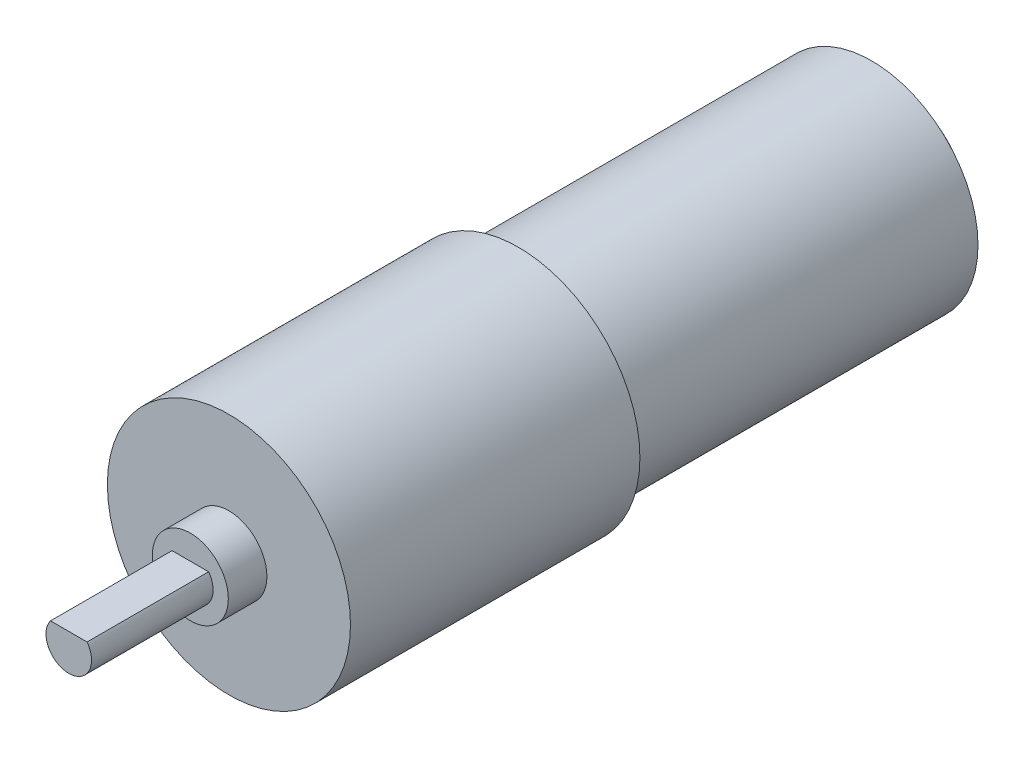
SolidWorks part; units mm, degrees
ref_plane "Front" through (0, 0, 0) normal (0, 0, 1) x (1, 0, 0)
ref_plane "Top" through (0, 0, 0) normal (0, 1, 0) x (1, 0, 0)
ref_plane "Right" through (0, 0, 0) normal (1, 0, 0) x (0, 0, -1)
sketch "Sketch2" plane through (0, 0, 0) normal (0, 0, 1) x (1, 0, 0)
  circle A0 centre (0, 0) radius 8
  dimension "D1" = 16
extrude "Base-Extrude" add sketch "Sketch2" against normal blind 19.05
sketch "Sketch3" plane through (0, 0, 0) normal (0, 0, 1) x (1, 0, 0)
  circle A0 centre (0, 0) radius 2.5
  dimension "D1" = 5
extrude "Boss-Extrude1" add sketch "Sketch3" along normal blind 2.54
sketch "Sketch5" plane through (0, 0, 2.54) normal (0, 0, 1) x (1, 0, 0)
  circle A0 centre (0, 0) radius 1.5
  dimension "D1" = 3
extrude "Boss-Extrude2" add sketch "Sketch5" along normal blind 8
sketch "Sketch6" plane through (0, 0, 10.54) normal (0, 0, 1) x (1, 0, 0)
  line L0 (-2.3343, 0.895) -> (2.3343, 0.895)
  arc A0 (2.3343, 0.895) -> (-2.3343, 0.895) centre (0, 0) ccw
  dimension "D2" = 2.5
  dimension "D1" = 0.895
extrude "Cut-Extrude1" cut sketch "Sketch6" against normal blind 8
sketch "Sketch7" plane through (0, 0, -19.05) normal (0, 0, -1) x (-1, 0, 0)
  circle A0 centre (0, 0) radius 7
  dimension "D1" = 14
extrude "Boss-Extrude3" add sketch "Sketch7" along normal blind 23.25
sketch "Sketch8" plane through (0, 0, -42.3) normal (0, 0, -1) x (-1, 0, 0)
  line L0 (3.2, 2.7048) -> (3.2, -2.7048)
  arc A0 (3.2, 2.7048) -> (3.2, -2.7048) centre (0, 0) ccw
  dimension "D2" = 8.38
  dimension "D1" = 3.2
extrude "Boss-Extrude4" add sketch "Sketch8" along normal blind 2
